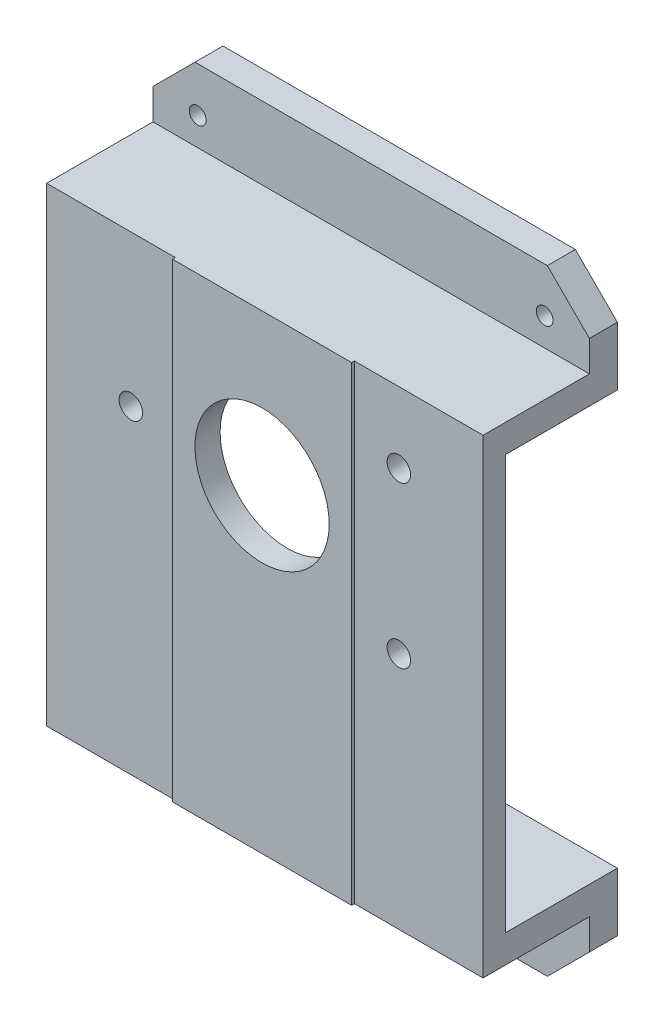
SolidWorks part; units mm, degrees
ref_plane "前视基准面" through (0, 0, 0) normal (0, 0, 1) x (1, 0, 0)
ref_plane "上视基准面" through (0, 0, 0) normal (0, 1, 0) x (1, 0, 0)
ref_plane "右视基准面" through (0, 0, 0) normal (1, 0, 0) x (0, 0, -1)
other "Configuration Table"
sketch "草图1" plane through (0, 0, 0) normal (0, 0, 1) x (1, 0, 0)
  line L0 (0, 0) -> (0, 50000) construction
  line L1 (31, -47) -> (-31, -47) construction
  line L2 (31, -47) -> (31, 47) construction
  line L3 (31, 47) -> (-31, 47) construction
  line L4 (-31, -47) -> (-31, 47) construction
  line L5 (31, -47) -> (-31, 47) construction
  line L6 (31, 47) -> (-31, -47) construction
  line L7 (-9.1849, 15) -> (49990.8151, 15) construction
  point P0 (0, 0)
  dimension "D1" = 62
  dimension "D2" = 94
  dimension "D3" = 32
sketch "草图2" plane through (0, 0, 0) normal (0, 0, 1) x (1, 0, 0)
  line L0 (31, 47) -> (-31, 47) construction
  line L1 (39, 42) -> (-39, 42)
  line L2 (39, 42) -> (39, 47.4853)
  line L3 (31.4853, 55) -> (-31.4853, 55)
  line L4 (-39, 42) -> (-39, 47.4853)
  line L8 (39, 47.4853) -> (31.4853, 55)
  line L9 (-39, 47.4853) -> (-31.4853, 55)
  line L10 (0, 0) -> (50000, 0) construction
  line L11 (31.4853, -55) -> (-31.4853, -55)
  line L12 (-39, -47.4853) -> (-31.4853, -55)
  line L13 (-39, -42) -> (-39, -47.4853)
  line L14 (39, -42) -> (-39, -42)
  line L15 (39, -47.4853) -> (31.4853, -55)
  line L16 (39, -42) -> (39, -47.4853)
  point P0 (0, 47)
  point P1 (-39, 55)
  point P3 (39, 55)
  dimension "D1" = 8
  dimension "D2" = 8
  dimension "D3" = 8
  dimension "D4" = 5
  dimension "D5" = 6
  dimension "D6" = 45
  dimension "D7" = 6
  dimension "D8" = 45
extrude "凸台-拉伸1" add sketch "草图2" along normal blind 5
sketch "草图3" plane through (-39, 0, 0) normal (-1, 0, 0) x (0, 0, 1)
  line L0 (0, 0) -> (50000, 0) construction
  line L1 (0, 42) -> (24, 42)
  line L2 (24, 42) -> (24, -42)
  line L3 (24, -42) -> (0, -42)
  line L4 (0, -42) -> (0, -37)
  line L5 (0, -47) -> (0, 47) construction
  line L6 (0, -37) -> (20, -37)
  line L7 (20, -37) -> (20, 37)
  line L8 (20, 37) -> (0, 37)
  line L9 (0, -47) -> (0, 47) construction
  line L10 (0, 37) -> (0, 42)
  dimension "D1" = 20
  dimension "D2" = 4
  dimension "D3" = 5
extrude "凸台-拉伸2" add sketch "草图3" against normal up to surface (78 mm away) up to face at (39, 44.7426, 2.5)
sketch "草图4" plane through (0, 0, 24) normal (0, 0, 1) x (1, 0, 0)
  line L0 (-200009.1849, 15) -> (249990.8151, 15) construction
  line L1 (-200009.1849, 15) -> (249990.8151, 15) construction
  line L2 (0, 0) -> (0, 50000) construction
  circle A0 centre (0, 15) radius 12
  dimension "D1" = 24
extrude "切除-拉伸1" cut sketch "草图4" against normal up to next
sketch "草图5" plane through (0, 0, 24) normal (0, 0, 1) x (1, 0, 0)
  line L0 (0, 15) -> (0, 50015) construction
  line L1 (0, 15) -> (50000, 15) construction
  line L4 (39, 42) -> (-39, 42) construction
  line L9 (-16, 42) -> (16, 42)
  line L10 (-16, 42) -> (-16, -42)
  line L11 (-16, -42) -> (16, -42)
  line L12 (16, 42) -> (16, -42)
  line L13 (39, -42) -> (-39, -42) construction
  circle A0 centre (0, 15) radius 12 construction
  circle A1 centre (0, 15) radius 12
  point P9 (0, 15)
  dimension "D1" = 32
extrude "凸台-拉伸3" add sketch "草图5" along normal blind 0.5
sketch "草图6" plane through (0, 0, 24) normal (0, 0, 1) x (1, 0, 0)
  line L0 (0, 15) -> (50000, 15) construction
  line L1 (0, 15) -> (0, 50015) construction
  line L5 (-23.95, 29.35) -> (23.95, 29.35) construction
  line L6 (-23.95, 29.35) -> (-23.95, 0.65) construction
  line L7 (-23.95, 0.65) -> (23.95, 0.65) construction
  line L8 (23.95, 29.35) -> (23.95, 0.65) construction
  circle A0 centre (-23.95, 15) radius 2.1
  circle A1 centre (23.95, 29.35) radius 2.1
  circle A2 centre (23.95, 0.65) radius 2.1
  dimension "D3" = 4.2
  dimension "D4" = 4.2
  dimension "D5" = 4.2
  dimension "D1" = 47.9
  dimension "D2" = 28.7
extrude "切除-拉伸2" cut sketch "草图6" against normal up to next
sketch "草图7" plane through (0, 0, 5) normal (0, 0, 1) x (1, 0, 0)
  line L0 (0, 15) -> (0, 50015) construction
  line L1 (0, 15) -> (50000, 15) construction
  line L2 (-31, 47) -> (-31, -47) construction
  line L3 (-31, -47) -> (31, -47) construction
  line L4 (31, -47) -> (31, 47) construction
  line L5 (31, 47) -> (-31, 47) construction
  circle A0 centre (-31, 47) radius 1.5
  circle A1 centre (31, 47) radius 1.5
  circle A2 centre (31, -47) radius 1.5
  circle A3 centre (-31, -47) radius 1.5
  point P0 (0, 15)
  dimension "D4" = 3
  dimension "D5" = 3
  dimension "D6" = 3
  dimension "D7" = 3
  dimension "D1" = 62
  dimension "D2" = 32
  dimension "D3" = 62
extrude "切除-拉伸3" cut sketch "草图7" against normal up to next
